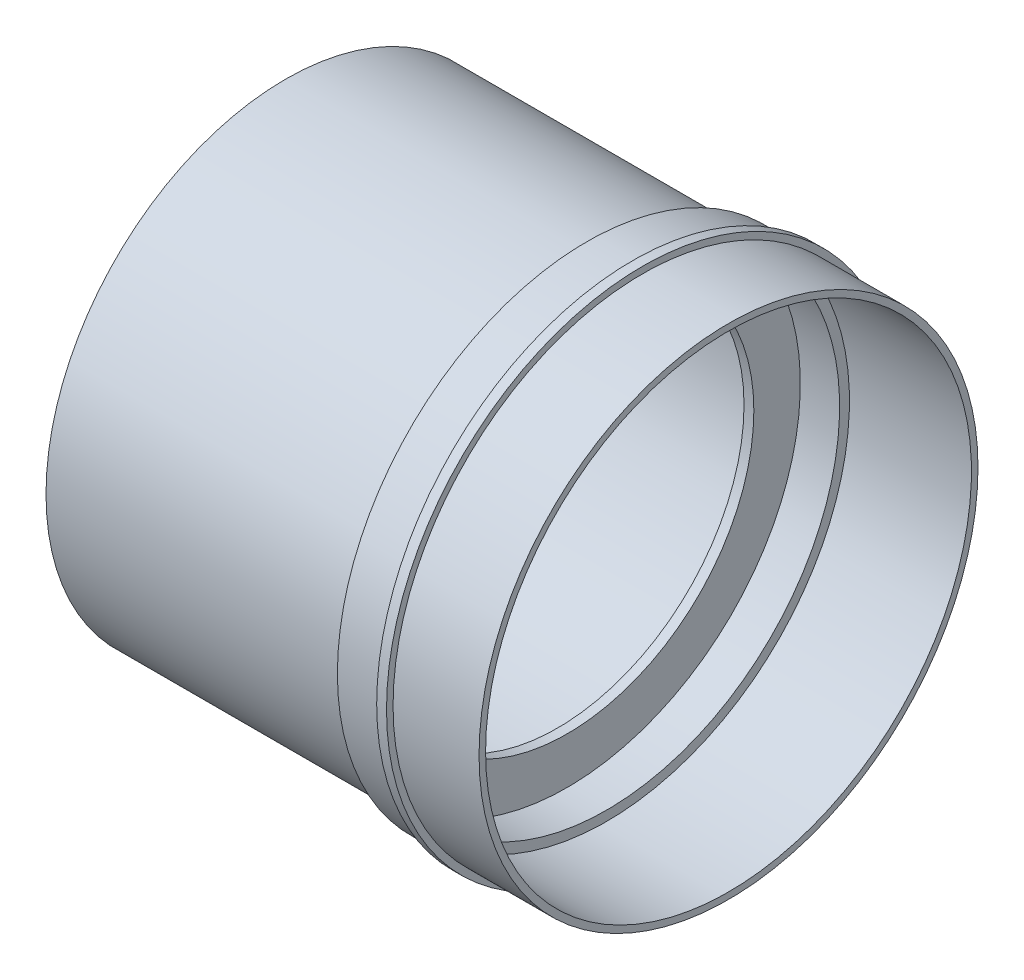
SolidWorks part; units mm, degrees
ref_plane "Front Plane" through (0, 0, 0) normal (0, 0, 1) x (1, 0, 0)
ref_plane "Top Plane" through (0, 0, 0) normal (0, 1, 0) x (1, 0, 0)
ref_plane "Right Plane" through (0, 0, 0) normal (1, 0, 0) x (0, 0, -1)
sketch "Sketch1" plane through (0, 0, 0) normal (0, 0, 1) x (1, 0, 0)
  line L0 (3, 71.2) -> (15, 71.2)
  line L1 (-83, 73.2) -> (9, 73.2)
  line L2 (-83, 73.2) -> (-83, 71.2)
  line L3 (-83, 71.2) -> (0, 71.2)
  line L4 (15, 74.2) -> (15, 71.2)
  line L5 (15, 74.2) -> (52.2635, 74.2)
  line L6 (9, 73.2) -> (9, 76.2)
  line L7 (9, 76.2) -> (23, 76.2)
  line L8 (52.2635, 74.2) -> (52.2635, 76.2)
  line L10 (23, 76.2) -> (23, 78.2)
  line L11 (23, 78.2) -> (26, 78.2)
  line L12 (26, 76.2) -> (26, 78.2)
  line L14 (0, 71.2) -> (0, 57)
  line L15 (0, 57) -> (3, 57)
  line L16 (3, 71.2) -> (3, 57)
  line L17 (-34.4738, 0) -> (63.6986, 0) construction
  line L18 (0, 57) -> (0, 0) construction
  line L19 (26, 76.2) -> (52.2635, 76.2)
  point P19 (9, 74.7)
  dimension "D1" = 2
  dimension "D2" = 57
  dimension "D3" = 73.2
  dimension "D4" = 2
  dimension "D5" = 2
  dimension "D6" = 3
  dimension "D7" = 3
  dimension "D8" = 92
  dimension "D9" = 3
  dimension "D10" = 6
  dimension "D11" = 6
  dimension "D12" = 14
revolve "Revolve1" add sketch "Sketch1" angle 360 about L17
